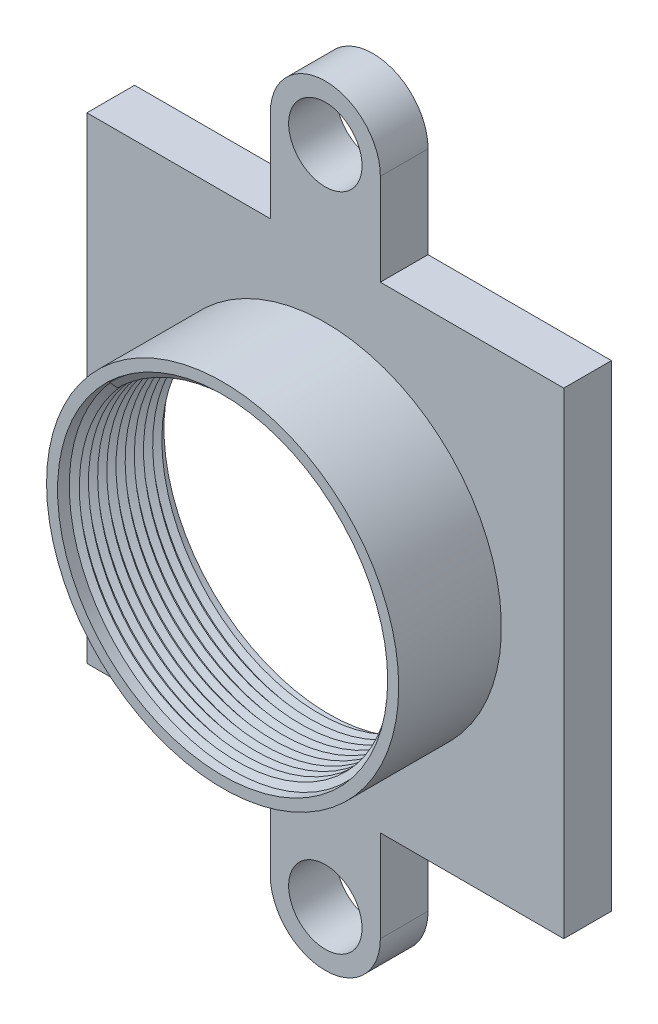
SolidWorks part; units mm, degrees
ref_plane "前视基准面" through (0, 0, 0) normal (0, 0, 1) x (1, 0, 0)
ref_plane "上视基准面" through (0, 0, 0) normal (0, 1, 0) x (1, 0, 0)
ref_plane "右视基准面" through (0, 0, 0) normal (1, 0, 0) x (0, 0, -1)
sketch "草图1" plane through (0, 0, 0) normal (0, 0, 1) x (1, 0, 0)
  line L0 (6.5, 6.5) -> (6.5, -6.5)
  line L1 (6, 6) -> (-6, 6)
  line L2 (6, 6) -> (6, -6)
  line L3 (6, -6) -> (-6, -6)
  line L4 (-6, 6) -> (-6, -6)
  line L5 (6, 6) -> (-6, -6) construction
  line L6 (6, -6) -> (-6, 6) construction
  line L7 (6.5, -6.5) -> (-6.5, -6.5)
  line L8 (-6.5, 6.5) -> (-6.5, -6.5)
  line L9 (6.5, 6.5) -> (-6.5, 6.5)
  point P0 (0, 0)
  dimension "D1" = 12
  dimension "D2" = 12
  dimension "D3" = 0.5
extrude "凸台-拉伸1" add sketch "草图1" along normal blind 1.2
sketch "草图2" plane through (0, 0, 1.2) normal (0, 0, 1) x (1, 0, 0)
  line L1 (-6.5, -6.5) -> (6.5, -6.5)
  line L2 (-6.5, -6.5) -> (-6.5, 6.5)
  line L3 (-6.5, 6.5) -> (6.5, 6.5)
  line L4 (6.5, -6.5) -> (6.5, 6.5)
  line L5 (-6.5, -6.5) -> (6.5, 6.5) construction
  line L6 (-6.5, 6.5) -> (6.5, -6.5) construction
  circle A1 centre (0, 0) radius 4.5
  point P0 (0, 0)
  dimension "D3" = 9
  dimension "D1" = 13
  dimension "D2" = 13
extrude "凸台-拉伸2" add sketch "草图2" along normal blind 0.1 contours A1
sketch "草图3" plane through (0, 6.5, 0) normal (0, 1, 0) x (1, 0, 0)
  line L0 (6.5, -1.3) -> (-6.5, -1.3) construction
  line L1 (1.5, 0) -> (-1.5, 0)
  line L2 (1.5, 0) -> (1.5, -1.3)
  line L3 (1.5, -1.3) -> (-1.5, -1.3)
  line L4 (-1.5, 0) -> (-1.5, -1.3)
  line L5 (1.5, 0) -> (-1.5, -1.3) construction
  line L6 (1.5, -1.3) -> (-1.5, 0) construction
  line L7 (6.5, 0) -> (-6.5, 0) construction
  point P0 (0, -0.65)
  dimension "D1" = 3
extrude "凸台-拉伸3" add sketch "草图3" along normal blind 4
sketch "草图4" plane through (0, 0, 1.3) normal (0, 0, 1) x (1, 0, 0)
  line L0 (-1.5, 9) -> (-1.5, 10.5)
  line L1 (-1.5, 10.5) -> (1.5, 10.5)
  line L2 (1.5, 10.5) -> (1.5, 9)
  circle A0 centre (0, 9) radius 1.5
  line M3 (1.5, 6.5) -> (1.5, 10.5)
  line M4 (1.5, 10.5) -> (-1.5, 10.5)
  line M5 (-1.5, 10.5) -> (-1.5, 6.5)
extrude "切除-拉伸1" cut sketch "草图4" against normal blind 4 contours A0 L1 M5 | A0 M3 M4
sketch "草图5" plane through (0, 0, 1.3) normal (0, 0, 1) x (1, 0, 0)
  circle A0 centre (0, 9) radius 1
  dimension "D2" = 2
  dimension "D1" = 9
extrude "切除-拉伸2" cut sketch "草图5" against normal blind 4 contours A0
mirror "镜向1" about plane through (0, 0, 0) normal (0, 1, 0) of "切除-拉伸1", "凸台-拉伸3", "切除-拉伸2"
sketch "草图6" plane through (0, 0, 1.3) normal (0, 0, 1) x (1, 0, 0)
  line L10 (1.5, -9) -> (1.5, -6.5)
  line L11 (1.5, -6.5) -> (6.5, -6.5)
  line L12 (6.5, -6.5) -> (6.5, 6.5)
  line L13 (6.5, 6.5) -> (1.5, 6.5)
  line L14 (1.5, 6.5) -> (1.5, 9)
  line L15 (-1.5, 9) -> (-1.5, 6.5)
  line L16 (-1.5, 6.5) -> (-6.5, 6.5)
  line L17 (-6.5, 6.5) -> (-6.5, -6.5)
  line L18 (-6.5, -6.5) -> (-1.5, -6.5)
  line L19 (-1.5, -6.5) -> (-1.5, -9)
  line L20 (1.5, -9) -> (1.5, -6.5)
  line L21 (1.5, -6.5) -> (6.5, -6.5)
  line L22 (6.5, -6.5) -> (6.5, 6.5)
  line L23 (6.5, 6.5) -> (1.5, 6.5)
  line L24 (1.5, 6.5) -> (1.5, 9)
  line L25 (-1.5, 9) -> (-1.5, 6.5)
  line L26 (-1.5, 6.5) -> (-6.5, 6.5)
  line L27 (-6.5, 6.5) -> (-6.5, -6.5)
  line L28 (-6.5, -6.5) -> (-1.5, -6.5)
  line L29 (-1.5, -6.5) -> (-1.5, -9)
  arc A2 (-1.5, -9) -> (1.5, -9) centre (0, -9) ccw
  arc A3 (1.5, 9) -> (-1.5, 9) centre (0, 9) ccw
  arc A4 (-1.5, -9) -> (1.5, -9) centre (0, -9) ccw
  arc A5 (1.5, 9) -> (-1.5, 9) centre (0, 9) ccw
  circle A6 centre (0, 0) radius 4.8
  circle A7 centre (0, 0) radius 4.8
  circle M26 centre (0, 0) radius 4.5
  dimension "D1" = 0
  dimension "D2" = 0.3
extrude "凸台-拉伸4" add sketch "草图6" along normal blind 2.8 contours A7 M26
sketch "草图7" plane through (0, 0, 1.2) normal (0, 0, -1) x (-1, 0, 0)
  circle A0 centre (0, 0) radius 4.5
curve "螺旋线/涡状线1" pitch 0.25 height 2.625 turns 10.5
sketch "草图8" plane through (0, 0, 0) normal (0, 1, 0) x (1, 0, 0)
  line L0 (-4.4773, -1.6023) -> (-4.4773, -1.8023)
  line L1 (-4.4773, -1.8023) -> (-4.3041, -1.7023)
  line L2 (-4.3041, -1.7023) -> (-4.4773, -1.6023)
  spline S0 degree 3 poles (3.182, -1.2) (3.5958, -1.2052) (4.2669, -1.2156) (4.6168, -1.2312) (4.2658, -1.2469) (3.2648, -1.2625) (1.7669, -1.2781) (0, -1.2937) (-1.7669, -1.3094) (-3.2648, -1.325) (-4.2657, -1.3406) (-4.6172, -1.3562) (-4.2657, -1.3719) (-3.2648, -1.3875) (-1.7669, -1.4031) (0, -1.4187) (1.7669, -1.4344) (3.2648, -1.45) (4.2657, -1.4656) (4.6172, -1.4812) (4.2657, -1.4969) (3.2648, -1.5125) (1.7669, -1.5281) (0, -1.5437) (-1.7669, -1.5594) (-3.2648, -1.575) (-4.2657, -1.5906) (-4.6172, -1.6062) (-4.2657, -1.6219) (-3.2648, -1.6375) (-1.7669, -1.6531) (0, -1.6687) (1.7669, -1.6844) (3.2648, -1.7) (4.2657, -1.7156) (4.6172, -1.7312) (4.2657, -1.7469) (3.2648, -1.7625) (1.7669, -1.7781) (0, -1.7937) (-1.7669, -1.8094) (-3.2648, -1.825) (-4.2657, -1.8406) (-4.6172, -1.8562) (-4.2657, -1.8719) (-3.2648, -1.8875) (-1.7669, -1.9031) (0, -1.9188) (1.7669, -1.9344) (3.2648, -1.95) (4.2657, -1.9656) (4.6172, -1.9813) (4.2657, -1.9969) (3.2648, -2.0125) (1.7669, -2.0281) (0, -2.0438) (-1.7669, -2.0594) (-3.2648, -2.075) (-4.2657, -2.0906) (-4.6172, -2.1063) (-4.2657, -2.1219) (-3.2648, -2.1375) (-1.7669, -2.1531) (0, -2.1688) (1.7669, -2.1844) (3.2648, -2.2) (4.2657, -2.2156) (4.6172, -2.2313) (4.2657, -2.2469) (3.2648, -2.2625) (1.7669, -2.2781) (0, -2.2938) (-1.7669, -2.3094) (-3.2648, -2.325) (-4.2657, -2.3406) (-4.6172, -2.3563) (-4.2657, -2.3719) (-3.2648, -2.3875) (-1.7669, -2.4031) (0, -2.4188) (1.7669, -2.4344) (3.2648, -2.45) (4.2657, -2.4656) (4.6172, -2.4813) (4.2657, -2.4969) (3.2648, -2.5125) (1.7669, -2.5281) (0, -2.5438) (-1.7669, -2.5594) (-3.2648, -2.575) (-4.2657, -2.5906) (-4.6172, -2.6063) (-4.2657, -2.6219) (-3.2648, -2.6375) (-1.7669, -2.6531) (0, -2.6688) (1.7669, -2.6844) (3.2648, -2.7) (4.2657, -2.7156) (4.6172, -2.7313) (4.2657, -2.7469) (3.2648, -2.7625) (1.7669, -2.7781) (0, -2.7938) (-1.7669, -2.8094) (-3.2648, -2.825) (-4.2657, -2.8406) (-4.6172, -2.8563) (-4.2657, -2.8719) (-3.2648, -2.8875) (-1.7669, -2.9031) (0, -2.9188) (1.7669, -2.9344) (3.2648, -2.95) (4.2657, -2.9656) (4.6172, -2.9813) (4.2657, -2.9969) (3.2648, -3.0125) (1.7669, -3.0281) (0, -3.0438) (-1.7669, -3.0594) (-3.2648, -3.075) (-4.2657, -3.0906) (-4.6172, -3.1063) (-4.2657, -3.1219) (-3.2648, -3.1375) (-1.7669, -3.1531) (0, -3.1688) (1.7669, -3.1844) (3.2648, -3.2) (4.2657, -3.2156) (4.6172, -3.2313) (4.2657, -3.2469) (3.2648, -3.2625) (1.7669, -3.2781) (0, -3.2938) (-1.7669, -3.3094) (-3.2648, -3.325) (-4.2657, -3.3406) (-4.6172, -3.3563) (-4.2657, -3.3719) (-3.2648, -3.3875) (-1.7669, -3.4031) (0, -3.4188) (1.7669, -3.4344) (3.2648, -3.45) (4.2657, -3.4656) (4.6172, -3.4813) (4.2657, -3.4969) (3.2648, -3.5125) (1.7669, -3.5281) (0, -3.5438) (-1.7669, -3.5594) (-3.2648, -3.575) (-4.2657, -3.5906) (-4.6172, -3.6063) (-4.2657, -3.6219) (-3.2648, -3.6375) (-1.7669, -3.6531) (0, -3.6688) (1.7669, -3.6844) (3.2648, -3.7) (4.2657, -3.7156) (4.6172, -3.7313) (4.2657, -3.7469) (3.2648, -3.7625) (1.767, -3.7781) (-0.0003, -3.7938) (-1.7657, -3.8094) (-2.7681, -3.8198) (-3.182, -3.825) knots 0 0 0 0 0.005952 0.011905 0.017857 0.02381 0.029762 0.035714 0.041667 0.047619 0.053571 0.059524 0.065476 0.071429 0.077381 0.083333 0.089286 0.095238 0.10119 0.107143 0.113095 0.119048 0.125 0.130952 0.136905 0.142857 0.14881 0.154762 0.160714 0.166667 0.172619 0.178571 0.184524 0.190476 0.196429 0.202381 0.208333 0.214286 0.220238 0.22619 0.232143 0.238095 0.244048 0.25 0.255952 0.261905 0.267857 0.27381 0.279762 0.285714 0.291667 0.297619 0.303571 0.309524 0.315476 0.321429 0.327381 0.333333 0.339286 0.345238 0.35119 0.357143 0.363095 0.369048 0.375 0.380952 0.386905 0.392857 0.39881 0.404762 0.410714 0.416667 0.422619 0.428571 0.434524 0.440476 0.446429 0.452381 0.458333 0.464286 0.470238 0.47619 0.482143 0.488095 0.494048 0.5 0.505952 0.511905 0.517857 0.52381 0.529762 0.535714 0.541667 0.547619 0.553571 0.559524 0.565476 0.571429 0.577381 0.583333 0.589286 0.595238 0.60119 0.607143 0.613095 0.619048 0.625 0.630952 0.636905 0.642857 0.64881 0.654762 0.660714 0.666667 0.672619 0.678571 0.684524 0.690476 0.696429 0.702381 0.708333 0.714286 0.720238 0.72619 0.732143 0.738095 0.744048 0.75 0.755952 0.761905 0.767857 0.77381 0.779762 0.785714 0.791667 0.797619 0.803571 0.809524 0.815476 0.821429 0.827381 0.833333 0.839286 0.845238 0.85119 0.857143 0.863095 0.869048 0.875 0.880952 0.886905 0.892857 0.89881 0.904762 0.910714 0.916667 0.922619 0.928571 0.934524 0.940476 0.946429 0.952381 0.958333 0.964286 0.970238 0.97619 0.982143 0.988095 0.994048 1 1 1 1 construction
  dimension "D1" = 120
  dimension "D2" = 120
  dimension "D3" = 0.2
sweep "扫描1" add profiles "草图8" path "螺旋线/涡状线1"
